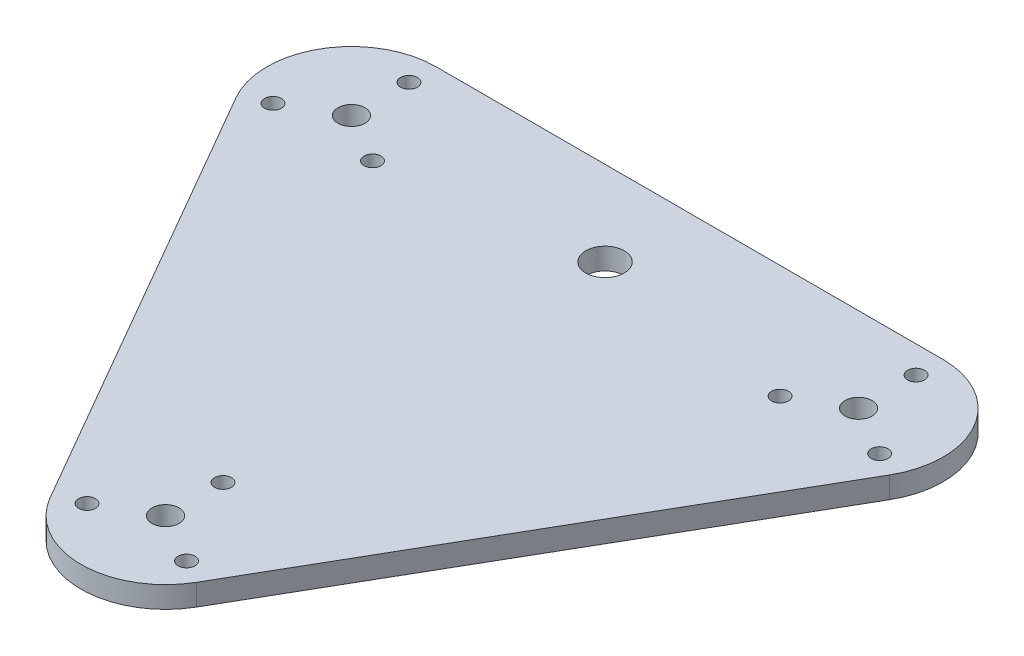
SolidWorks part; units mm, degrees
ref_plane "Plan de face" through (0, 0, 0) normal (0, 0, 1) x (1, 0, 0)
ref_plane "Plan de dessus" through (0, 0, 0) normal (0, 1, 0) x (1, 0, 0)
ref_plane "Plan de droite" through (0, 0, 0) normal (1, 0, 0) x (0, 0, -1)
sketch "Esquisse1" plane through (0, 0, 0) normal (0, 1, 0) x (1, 0, 0)
  line L0 (-96.6546, 52.5069) -> (-21.6546, -77.4931)
  line L1 (96.6546, 52.5069) -> (21.6546, -77.4931)
  line L2 (-75, 90) -> (75, 90)
  line L3 (75, 65) -> (-75, 65) construction
  arc A3 (-75, 90) -> (-96.6546, 52.5069) centre (-75, 65) ccw
  arc A4 (96.6546, 52.5069) -> (75, 90) centre (75, 65) ccw
  arc A5 (-21.6546, -77.4931) -> (21.6546, -77.4931) centre (0, -65) ccw
  circle A6 centre (0, 65) radius 5.7
  circle A7 centre (-75, 65) radius 4
  circle A8 centre (75, 65) radius 4
  circle A9 centre (0, -65) radius 4
  dimension "D1" = 11.4
  dimension "D6" = 50
  dimension "D7" = 8
  dimension "D2" = 65
  dimension "D3" = 65
  dimension "D4" = 150
  dimension "D5" = 75
extrude "Boss.-Extru.1" add sketch "Esquisse1" along normal blind 6.35
sketch "Esquisse4" plane through (0, 0, 0) normal (0, -1, 0) x (1, 0, 0)
  circle A0 centre (-75, -82) radius 2.5
  circle A1 centre (-89.7224, -56.5) radius 2.5
  circle A2 centre (-60.2776, -56.5) radius 2.5
  circle A3 centre (60.2776, -56.5) radius 2.5
  circle A4 centre (75, -82) radius 2.5
  circle A5 centre (89.7224, -56.5) radius 2.5
  circle A6 centre (-14.7224, 73.5) radius 2.5
  circle A7 centre (0, 48) radius 2.5
  circle A8 centre (14.7224, 73.5) radius 2.5
extrude "Enlèv. mat.-Extru.1" cut sketch "Esquisse4" along a picked direction on the side against the normal blind 6.35
